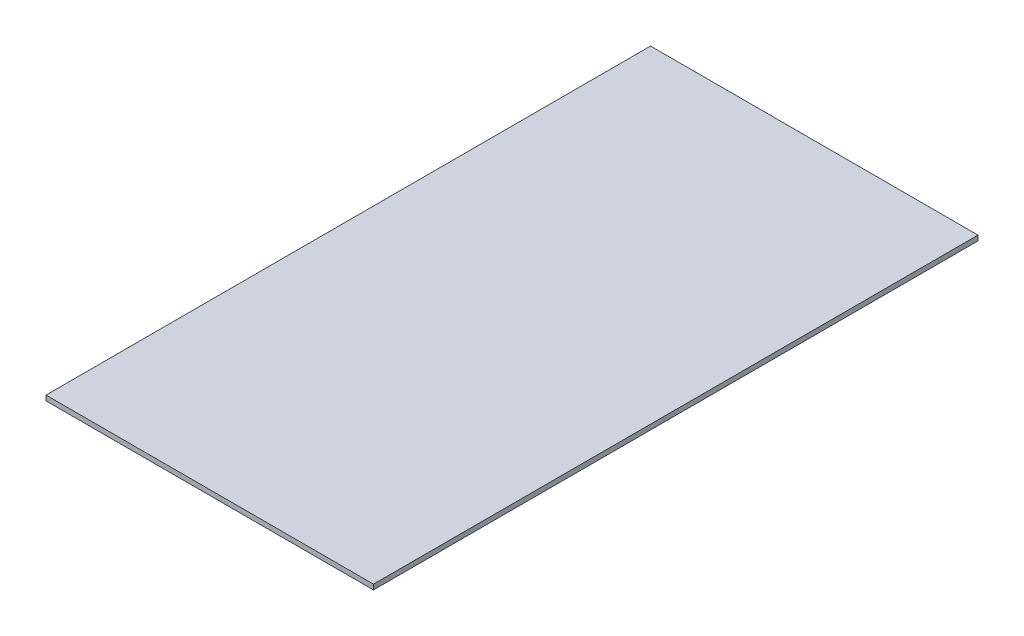
SolidWorks part; units mm, degrees
ref_plane "Front Plane" through (0, 0, 0) normal (0, 0, 1) x (1, 0, 0)
ref_plane "Top Plane" through (0, 0, 0) normal (0, 1, 0) x (1, 0, 0)
ref_plane "Right Plane" through (0, 0, 0) normal (1, 0, 0) x (0, 0, -1)
sketch "Sketch1" plane through (0, 0, 0) normal (0, 1, 0) x (1, 0, 0)
  line L1 (-32.5, 60) -> (32.5, 60)
  line L2 (-32.5, 60) -> (-32.5, -60)
  line L3 (-32.5, -60) -> (32.5, -60)
  line L4 (32.5, 60) -> (32.5, -60)
  line L5 (-32.5, 60) -> (32.5, -60) construction
  line L6 (-32.5, -60) -> (32.5, 60) construction
  point P0 (0, 0)
  dimension "D1" = 65
  dimension "D2" = 120
extrude "Boss-Extrude1" add sketch "Sketch1" along normal blind 1
